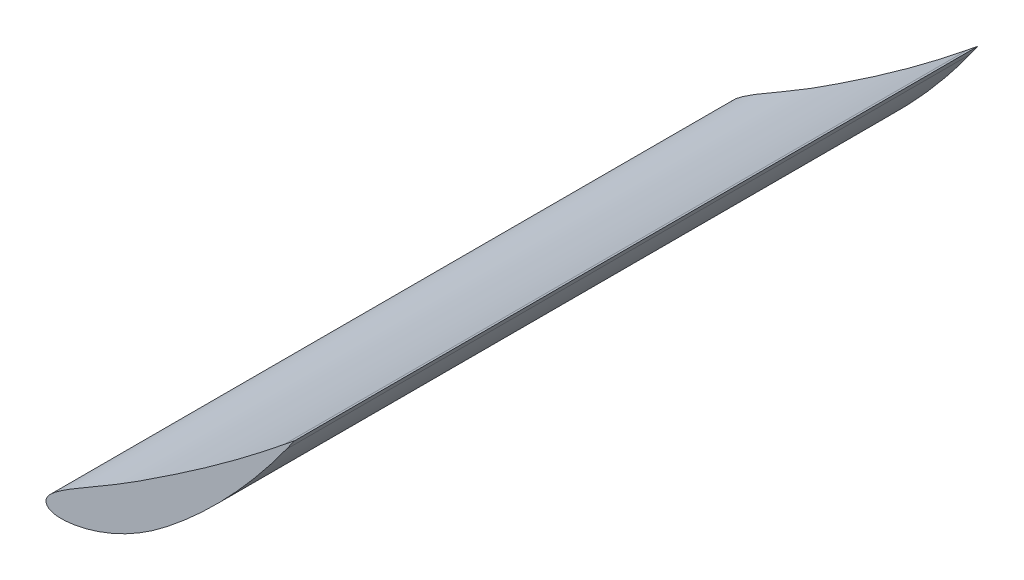
SolidWorks part; units mm, degrees
ref_plane "Front Plane" through (0, 0, 0) normal (0, 0, 1) x (1, 0, 0)
ref_plane "Top Plane" through (0, 0, 0) normal (0, 1, 0) x (1, 0, 0)
ref_plane "Right Plane" through (0, 0, 0) normal (1, 0, 0) x (0, 0, -1)
sketch "Sketch3" plane through (0, 0, 0) normal (0, 0, 1) x (1, 0, 0)
  line L7 (0, 0) -> (143.0551, 0) construction
  line L14 (0, 0) -> (-43.0922, 59.3113) construction
  line L16 (147.6263, 106.7445) -> (154.1177, 111.9731)
  line L17 (154.1177, 111.9731) -> (148.9789, 104.8432)
  line L19 (0, 0) -> (154.1177, 111.9731) construction
  spline S1 degree 3 poles (148.9789, 104.8432) (147.8347, 103.2557) (146.6853, 101.673) (144.3619, 98.53) (143.1902, 96.9677) (139.645, 92.3082) (137.2419, 89.2382) (129.914, 80.1367) (124.8717, 74.2127) (114.4671, 62.6576) (109.1052, 57.0262) (98.0326, 46.0824) (92.3225, 40.7696) (84.9301, 34.3617) (83.4378, 33.091) (80.4308, 30.5791) (78.9169, 29.339) (74.3452, 25.6644) (71.2639, 23.266) (64.938, 18.7184) (61.6998, 16.5595) (55.0617, 12.4887) (51.6616, 10.577) (46.426, 7.9163) (44.6582, 7.064) (41.0737, 5.4339) (39.2615, 4.6583) (33.7894, 2.4694) (30.0843, 1.1866) (24.4212, -0.4117) (22.5158, -0.8897) (19.6251, -1.5062) (18.6545, -1.6949) (16.7105, -2.0319) (15.7369, -2.1801) (13.786, -2.4286) (12.8087, -2.5294) (10.8495, -2.6699) (9.8677, -2.7107) (8.3899, -2.7081) (7.8965, -2.6966) (6.9077, -2.6474) (6.4109, -2.6092) (5.4244, -2.4975) (4.9341, -2.4249) (3.962, -2.2323) (3.4785, -2.1111) (2.532, -1.8023) (2.0729, -1.616) (1.4185, -1.259) (1.2049, -1.1262) (0.8011, -0.8353) (0.6104, -0.6769) (0.2568, -0.328) (0.0925, -0.1354) (-0.1906, 0.2736) (-0.311, 0.4904) (-0.5078, 0.9494) (-0.5828, 1.1902) (-0.6771, 1.6759) (-0.6966, 1.925) (-0.6836, 2.4265) (-0.6519, 2.6726) (-0.5486, 3.1574) (-0.4765, 3.3976) (-0.212, 4.0983) (0.0255, 4.5319) (0.5679, 5.3619) (0.8726, 5.7584) (1.5133, 6.5079) (1.8506, 6.8647) (2.895, 7.9011) (3.6359, 8.545) (5.1614, 9.7868) (5.9488, 10.383) (8.3374, 12.1172) (9.9717, 13.2053) (13.2757, 15.3243) (14.9465, 16.3533) (18.3057, 18.3829) (19.9945, 19.3828) (25.0724, 22.3638) (28.4723, 24.3276) (35.2568, 28.2797) (38.6415, 30.2667) (45.3708, 34.2997) (48.7155, 36.3456) (53.6908, 39.4753) (55.3423, 40.5288) (58.6292, 42.6592) (60.2651, 43.7355) (65.1708, 46.9672) (68.4409, 49.1224) (78.2238, 55.6279) (84.715, 60.0097) (97.5965, 68.9217) (103.9867, 73.4516) (116.6504, 82.6829) (122.9243, 87.3833) (132.2499, 94.559) (135.345, 96.9715) (139.9658, 100.617) (141.5025, 101.8368) (144.5692, 104.2846) (146.0984, 105.5138) (147.6263, 106.7445) knots 0 0 0 0 0.015625 0.015625 0.03125 0.03125 0.0625 0.0625 0.125 0.125 0.1875 0.1875 0.25 0.25 0.265625 0.265625 0.28125 0.28125 0.3125 0.3125 0.34375 0.34375 0.375 0.375 0.390625 0.390625 0.40625 0.40625 0.4375 0.4375 0.453125 0.453125 0.460937 0.460937 0.46875 0.46875 0.476562 0.476562 0.484375 0.484375 0.488281 0.488281 0.492187 0.492187 0.496094 0.496094 0.5 0.5 0.503906 0.503906 0.505859 0.505859 0.507812 0.507812 0.509766 0.509766 0.511719 0.511719 0.513672 0.513672 0.515625 0.515625 0.517578 0.517578 0.519531 0.519531 0.523437 0.523437 0.527344 0.527344 0.53125 0.53125 0.539062 0.539062 0.546875 0.546875 0.5625 0.5625 0.578125 0.578125 0.59375 0.59375 0.625 0.625 0.65625 0.65625 0.6875 0.6875 0.703125 0.703125 0.71875 0.71875 0.75 0.75 0.8125 0.8125 0.875 0.875 0.9375 0.9375 0.96875 0.96875 0.984375 0.984375 1 1 1 1
  dimension "D1" = 126
  dimension "D2" = 190.5
extrude "Boss-Extrude3" add sketch "Sketch3" along normal blind 425.45
sketch "Sketch4" plane through (0, 0, 0) normal (0, 0, -1) x (-1, 0, 0)
  line L0 (0, 0) -> (-154.1177, 111.9731) construction
sketch "Sketch5" plane through (0, 0, 425.45) normal (0, 0, 1) x (1, 0, 0)
  line L0 (0, 0) -> (154.1177, 111.9731) construction
